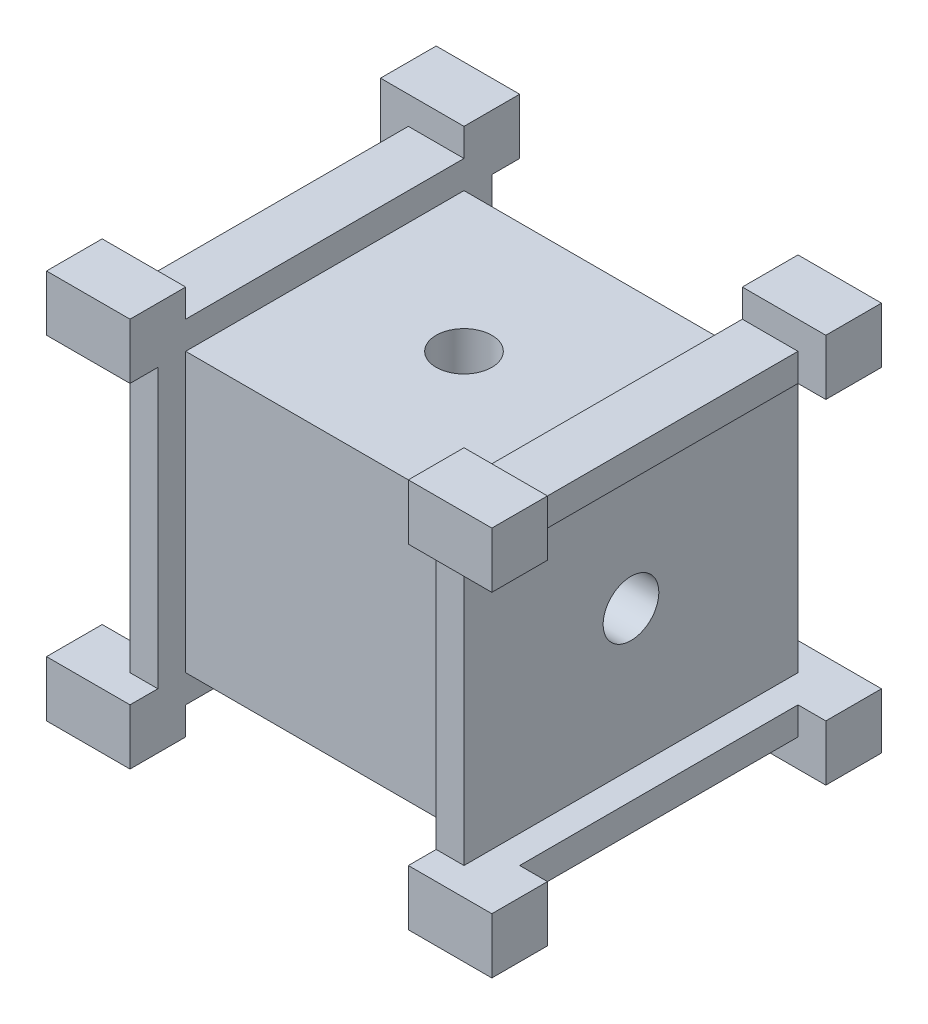
SolidWorks part; units mm, degrees
ref_plane "Front Plane" through (0, 0, 0) normal (0, 0, 1) x (1, 0, 0)
ref_plane "Top Plane" through (0, 0, 0) normal (0, 1, 0) x (1, 0, 0)
ref_plane "Right Plane" through (0, 0, 0) normal (1, 0, 0) x (0, 0, -1)
sketch "Sketch1" plane through (0, 0, 0) normal (0, 0, 1) x (1, 0, 0)
  line L1 (6, -6) -> (-6, -6)
  line L2 (6, -6) -> (6, 6)
  line L3 (6, 6) -> (-6, 6)
  line L4 (-6, -6) -> (-6, 6)
  line L5 (6, -6) -> (-6, 6) construction
  line L6 (6, 6) -> (-6, -6) construction
  point P0 (0, 0)
  dimension "D1" = 12
  dimension "D2" = 12
extrude "Boss-Extrude1" add sketch "Sketch1" along normal blind 12
sketch "Sketch2" plane through (0, 0, 12) normal (0, 0, 1) x (1, 0, 0)
  line L1 (-5, 6) -> (5, 6)
  line L2 (-5, 6) -> (-5, -6)
  line L3 (-5, -6) -> (5, -6)
  line L4 (5, 6) -> (5, -6)
  line L5 (-5, 6) -> (5, -6) construction
  line L6 (-5, -6) -> (5, 6) construction
  point P0 (0, 0)
  dimension "D1" = 10
  dimension "D2" = 12
extrude "Cut-Extrude1" cut sketch "Sketch2" against normal blind 1
sketch "Sketch3" plane through (0, -6, 0) normal (0, -1, 0) x (-1, 0, 0)
  line L0 (5, -11) -> (-5, -11)
  line L1 (5, -11) -> (5, 0)
  line L2 (-5, -11) -> (-5, 0)
  line L3 (5, 0) -> (-5, 0)
  line L4 (6, 0) -> (-6, 0) construction
  dimension "D1" = 10
  dimension "D2" = 11
extrude "Cut-Extrude2" cut sketch "Sketch3" against normal blind 1
sketch "Sketch4" plane through (0, 0, 0) normal (0, 0, -1) x (-1, 0, 0)
  line L0 (5, -5) -> (-5, -5)
  line L1 (5, -5) -> (5, 6)
  line L2 (-5, -5) -> (-5, 6)
  line L3 (5, 6) -> (-5, 6)
  line L4 (-6, 6) -> (6, 6) construction
  dimension "D1" = 10
  dimension "D2" = 11
extrude "Cut-Extrude3" cut sketch "Sketch4" against normal blind 1
sketch "Sketch5" plane through (0, 6, 0) normal (0, 1, 0) x (1, 0, 0)
  line L0 (-5, -11) -> (-5, -1)
  line L1 (-5, -11) -> (5, -11)
  line L2 (-5, -1) -> (5, -1)
  line L3 (5, -11) -> (5, -1)
  line L4 (5, -11) -> (-5, -11) construction
  dimension "D1" = 10
  dimension "D2" = 10
extrude "Cut-Extrude4" cut sketch "Sketch5" against normal blind 1
sketch "Sketch6" plane through (-6, 0, 0) normal (-1, 0, 0) x (0, 0, 1)
  line L0 (0, -6) -> (0, -5)
  line L1 (0, -6) -> (12, -6)
  line L2 (0, -5) -> (12, -5)
  line L3 (12, -6) -> (12, -5)
  line L4 (0, 6) -> (0, -6) construction
  line L6 (12, 6) -> (12, -6) construction
  dimension "D1" = 12
  dimension "D2" = 1
extrude "Boss-Extrude2" add sketch "Sketch6" along normal blind 1
sketch "Sketch7" plane through (-6, 0, 0) normal (-1, 0, 0) x (0, 0, 1)
  line L0 (0, 6) -> (0, 5)
  line L1 (0, 6) -> (12, 6)
  line L2 (0, 5) -> (12, 5)
  line L3 (12, 6) -> (12, 5)
  line L4 (0, 6) -> (0, -5) construction
  line L6 (12, 6) -> (12, -5) construction
  dimension "D1" = 12
  dimension "D2" = 1
extrude "Boss-Extrude3" add sketch "Sketch7" along normal blind 1
sketch "Sketch8" plane through (6, 0, 0) normal (1, 0, 0) x (0, 0, -1)
  line L0 (0, 6) -> (0, 5)
  line L1 (0, 6) -> (-12, 6)
  line L2 (0, 5) -> (-12, 5)
  line L3 (-12, 6) -> (-12, 5)
  line L4 (0, -6) -> (0, 6) construction
  line L6 (-12, -6) -> (-12, 6) construction
  line L7 (0, -6) -> (0, -5)
  line L8 (0, -6) -> (-12, -6)
  line L9 (0, -5) -> (-12, -5)
  line L10 (-12, -6) -> (-12, -5)
  dimension "D1" = 12
  dimension "D2" = 1
extrude "Boss-Extrude4" add sketch "Sketch8" along normal blind 1
sketch "Sketch12" plane through (0, -6, 0) normal (0, -1, 0) x (-1, 0, 0)
  line L0 (-7, 0) -> (-5, 0)
  line L1 (-7, 0) -> (-7, -1)
  line L2 (-5, 0) -> (-5, -1)
  line L3 (-7, -1) -> (-5, -1)
  line L4 (-5, 0) -> (-5, -12) construction
  line L5 (-7, -12) -> (-7, 0) construction
  dimension "D1" = 1
  dimension "D2" = 2
extrude "Boss-Extrude5" add sketch "Sketch12" along normal blind 1
sketch "Sketch13" plane through (0, -6, 0) normal (0, -1, 0) x (-1, 0, 0)
  line L0 (-7, -12) -> (-7, -11)
  line L1 (-7, -12) -> (-5, -12)
  line L2 (-7, -11) -> (-5, -11)
  line L3 (-5, -12) -> (-5, -11)
  line L4 (-7, -12) -> (-7, -1) construction
  line L6 (-5, -1) -> (-5, -12) construction
  dimension "D1" = 1
  dimension "D2" = 2
extrude "Boss-Extrude6" add sketch "Sketch13" along normal blind 1
sketch "Sketch14" plane through (0, -6, 0) normal (0, -1, 0) x (-1, 0, 0)
  line L0 (5, 0) -> (7, 0)
  line L1 (5, 0) -> (5, -1)
  line L2 (7, 0) -> (7, -1)
  line L3 (5, -1) -> (7, -1)
  dimension "D1" = 2
  dimension "D2" = 1
extrude "Boss-Extrude7" add sketch "Sketch14" along normal blind 1
sketch "Sketch16" plane through (0, -6, 0) normal (0, -1, 0) x (-1, 0, 0)
  line L0 (5, -12) -> (5, -11)
  line L1 (5, -12) -> (7, -12)
  line L2 (5, -11) -> (7, -11)
  line L3 (7, -12) -> (7, -11)
  line L4 (5, -1) -> (5, -12) construction
  line L6 (7, -1) -> (7, -12) construction
  dimension "D1" = 2
  dimension "D2" = 1
extrude "Boss-Extrude8" add sketch "Sketch16" along normal blind 1
sketch "Sketch19" plane through (0, 6, 0) normal (0, 1, 0) x (1, 0, 0)
  line L0 (7, -12) -> (5, -12)
  line L1 (7, -12) -> (7, -11)
  line L2 (5, -12) -> (5, -11)
  line L3 (7, -11) -> (5, -11)
  line L4 (5, 0) -> (5, -12) construction
  dimension "D1" = 2
  dimension "D2" = 1
extrude "Boss-Extrude10" add sketch "Sketch19" along normal blind 1
sketch "Sketch20" plane through (0, 6, 0) normal (0, 1, 0) x (1, 0, 0)
  line L0 (-5, -12) -> (-7, -12)
  line L1 (-5, -12) -> (-5, -11)
  line L2 (-7, -12) -> (-7, -11)
  line L3 (-5, -11) -> (-7, -11)
  line L4 (-7, -12) -> (-7, 0) construction
  line L5 (-5, 0) -> (-5, -12) construction
  dimension "D1" = 2
  dimension "D2" = 1
extrude "Boss-Extrude11" add sketch "Sketch20" along normal blind 1
sketch "Sketch21" plane through (0, 6, 0) normal (0, 1, 0) x (1, 0, 0)
  line L0 (7, 0) -> (7, -1)
  line L1 (7, 0) -> (5, 0)
  line L2 (7, -1) -> (5, -1)
  line L3 (5, 0) -> (5, -1)
  line L4 (7, 0) -> (7, -11) construction
  line L6 (5, 0) -> (5, -11) construction
  dimension "D1" = 2
  dimension "D2" = 1
extrude "Boss-Extrude12" add sketch "Sketch21" along normal blind 1
sketch "Sketch22" plane through (0, 6, 0) normal (0, 1, 0) x (1, 0, 0)
  line L0 (-5, 0) -> (-5, -1)
  line L1 (-5, 0) -> (-7, 0)
  line L2 (-5, -1) -> (-7, -1)
  line L3 (-7, 0) -> (-7, -1)
  line L4 (-5, 0) -> (-5, -11) construction
  line L6 (-7, -11) -> (-7, 0) construction
  dimension "D1" = 2
  dimension "D2" = 1
extrude "Boss-Extrude13" add sketch "Sketch22" along normal blind 1
sketch "Sketch23" plane through (7, 0, 0) normal (1, 0, 0) x (0, 0, -1)
  line L0 (-12, 7) -> (-11, 7)
  line L1 (-12, 7) -> (-12, 5)
  line L2 (-11, 7) -> (-11, 5)
  line L3 (-12, 5) -> (-11, 5)
  line L4 (-12, 5) -> (0, 5) construction
  dimension "D1" = 2
  dimension "D2" = 1
extrude "Boss-Extrude15" add sketch "Sketch23" along normal blind 1
sketch "Sketch24" plane through (0, 0, 12) normal (0, 0, 1) x (1, 0, 0)
  line L0 (8, 7) -> (5, 7)
  line L1 (8, 7) -> (8, 5)
  line L2 (5, 7) -> (5, 5)
  line L3 (8, 5) -> (5, 5)
  line L4 (5, -7) -> (5, 7) construction
  line L5 (5, 7) -> (8, 7) construction
  line L6 (8, 5) -> (6, 5) construction
  dimension "D1" = 3
  dimension "D2" = 2
  dimension "D3" = 2
extrude "Boss-Extrude16" add sketch "Sketch24" along normal blind 1
sketch "Sketch25" plane through (7, 0, 0) normal (1, 0, 0) x (0, 0, -1)
  line L0 (-11, -7) -> (-12, -7)
  line L1 (-11, -7) -> (-11, -5)
  line L2 (-12, -7) -> (-12, -5)
  line L3 (-11, -5) -> (-12, -5)
  line L4 (0, -5) -> (-12, -5) construction
  dimension "D1" = 2
  dimension "D2" = 1
extrude "Boss-Extrude17" add sketch "Sketch25" along normal blind 1
sketch "Sketch26" plane through (7, 0, 0) normal (1, 0, 0) x (0, 0, -1)
  line L0 (0, -7) -> (-1, -7)
  line L1 (0, -7) -> (0, -5)
  line L2 (-1, -7) -> (-1, -5)
  line L3 (0, -5) -> (-1, -5)
  line L4 (0, -5) -> (-11, -5) construction
  dimension "D1" = 2
  dimension "D2" = 1
extrude "Boss-Extrude19" add sketch "Sketch26" along normal blind 1
sketch "Sketch28" plane through (7, 0, 0) normal (1, 0, 0) x (0, 0, -1)
  line L0 (0, 7) -> (-1, 7)
  line L1 (0, 7) -> (0, 5)
  line L2 (-1, 7) -> (-1, 5)
  line L3 (0, 5) -> (-1, 5)
  line L4 (-11, 5) -> (0, 5) construction
  dimension "D1" = 2
  dimension "D2" = 1
extrude "Boss-Extrude20" add sketch "Sketch28" along normal blind 1
sketch "Sketch29" plane through (-7, 0, 0) normal (-1, 0, 0) x (0, 0, 1)
  line L0 (0, 7) -> (0, 5)
  line L1 (0, 7) -> (1, 7)
  line L2 (0, 5) -> (1, 5)
  line L3 (1, 7) -> (1, 5)
  dimension "D1" = 2
  dimension "D2" = 1
extrude "Boss-Extrude21" add sketch "Sketch29" along normal blind 1
sketch "Sketch30" plane through (-7, 0, 0) normal (-1, 0, 0) x (0, 0, 1)
  line L0 (12, 7) -> (11, 7)
  line L1 (12, 7) -> (12, 5)
  line L2 (11, 7) -> (11, 5)
  line L3 (12, 5) -> (11, 5)
  line L4 (11, 7) -> (12, 7) construction
  line L6 (1, 5) -> (12, 5) construction
  line L7 (11, 7) -> (11, 6) construction
  dimension "D1" = 2
  dimension "D2" = 1
extrude "Boss-Extrude22" add sketch "Sketch30" along normal blind 1
sketch "Sketch31" plane through (-7, 0, 0) normal (-1, 0, 0) x (0, 0, 1)
  line L0 (0, -7) -> (1, -7)
  line L1 (0, -7) -> (0, -5)
  line L2 (1, -7) -> (1, -5)
  line L3 (0, -5) -> (1, -5)
  line L4 (0, -5) -> (0, -7) construction
  line L6 (12, -5) -> (0, -5) construction
  dimension "D1" = 2
  dimension "D2" = 1
extrude "Boss-Extrude24" add sketch "Sketch31" along normal blind 1
sketch "Sketch33" plane through (-7, 0, 0) normal (-1, 0, 0) x (0, 0, 1)
  line L0 (11, -7) -> (12, -7)
  line L1 (11, -7) -> (11, -5)
  line L2 (12, -7) -> (12, -5)
  line L3 (11, -5) -> (12, -5)
  line L4 (12, -5) -> (1, -5) construction
  dimension "D1" = 2
  dimension "D2" = 1
extrude "Boss-Extrude25" add sketch "Sketch33" along normal blind 1
sketch "Sketch34" plane through (0, 0, 12) normal (0, 0, 1) x (1, 0, 0)
  line L0 (-8, 5) -> (-8, 7)
  line L1 (-8, 5) -> (-5, 5)
  line L2 (-8, 7) -> (-5, 7)
  line L3 (-5, 5) -> (-5, 7)
  line L4 (-5, 7) -> (-5, -7) construction
  dimension "D1" = 3
  dimension "D2" = 2
extrude "Boss-Extrude26" add sketch "Sketch34" along normal blind 1
sketch "Sketch35" plane through (0, 0, 12) normal (0, 0, 1) x (1, 0, 0)
  line L0 (-8, -7) -> (-8, -5)
  line L1 (-8, -7) -> (-5, -7)
  line L2 (-8, -5) -> (-5, -5)
  line L3 (-5, -7) -> (-5, -5)
  line L4 (-5, 5) -> (-5, -7) construction
  dimension "D1" = 3
  dimension "D2" = 2
extrude "Boss-Extrude27" add sketch "Sketch35" along normal blind 1
sketch "Sketch36" plane through (0, 0, 12) normal (0, 0, 1) x (1, 0, 0)
  line L0 (8, -5) -> (8, -7)
  line L1 (8, -5) -> (5, -5)
  line L2 (8, -7) -> (5, -7)
  line L3 (5, -5) -> (5, -7)
  line L4 (5, -7) -> (5, 5) construction
  dimension "D1" = 3
  dimension "D2" = 2
extrude "Boss-Extrude28" add sketch "Sketch36" along normal blind 1
sketch "Sketch37" plane through (0, 0, 0) normal (0, 0, -1) x (-1, 0, 0)
  line L0 (-8, 7) -> (-5, 7)
  line L1 (-8, 7) -> (-8, 5)
  line L2 (-5, 7) -> (-5, 5)
  line L3 (-8, 5) -> (-5, 5)
  line L4 (-5, 7) -> (-5, -7) construction
  dimension "D1" = 2
  dimension "D2" = 3
extrude "Boss-Extrude29" add sketch "Sketch37" along normal blind 1
sketch "Sketch38" plane through (0, 0, 0) normal (0, 0, -1) x (-1, 0, 0)
  line L0 (-8, -7) -> (-8, -5)
  line L1 (-8, -7) -> (-5, -7)
  line L2 (-8, -5) -> (-5, -5)
  line L3 (-5, -7) -> (-5, -5)
  line L4 (-5, 5) -> (-5, -7) construction
  dimension "D1" = 3
  dimension "D2" = 2
extrude "Boss-Extrude30" add sketch "Sketch38" along normal blind 1
sketch "Sketch39" plane through (0, 0, 0) normal (0, 0, -1) x (-1, 0, 0)
  line L0 (8, -5) -> (8, -7)
  line L1 (8, -5) -> (5, -5)
  line L2 (8, -7) -> (5, -7)
  line L3 (5, -5) -> (5, -7)
  line L4 (5, 7) -> (5, -7) construction
  dimension "D1" = 3
  dimension "D2" = 2
extrude "Boss-Extrude31" add sketch "Sketch39" along normal blind 1
sketch "Sketch40" plane through (0, 0, 0) normal (0, 0, -1) x (-1, 0, 0)
  line L0 (8, 7) -> (8, 5)
  line L1 (8, 7) -> (5, 7)
  line L2 (8, 5) -> (5, 5)
  line L3 (5, 7) -> (5, 5)
  line L4 (5, 7) -> (5, -5) construction
  dimension "D1" = 3
  dimension "D2" = 2
extrude "Boss-Extrude32" add sketch "Sketch40" along normal blind 1
sketch "Sketch41" plane through (6, 0, 0) normal (1, 0, 0) x (0, 0, -1)
  circle A0 centre (-6, 0) radius 1
  dimension "D1" = 2
extrude "Cut-Extrude6" cut sketch "Sketch41" against normal blind 12
sketch "Sketch42" plane through (0, -5, 0) normal (0, -1, 0) x (-1, 0, 0)
  circle A0 centre (0, -6) radius 1
  dimension "D1" = 2
extrude "Cut-Extrude7" cut sketch "Sketch42" against normal blind 12
